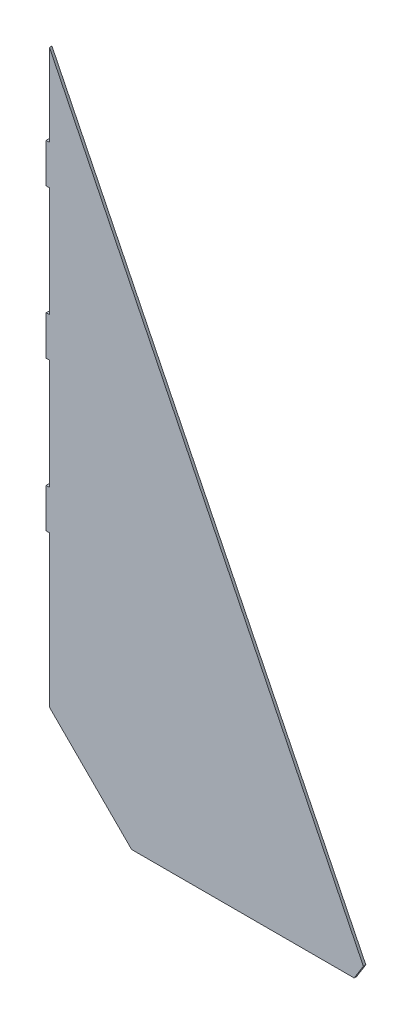
SolidWorks part; units mm, degrees
ref_plane "Front Plane" through (0, 0, 0) normal (0, 0, 1) x (1, 0, 0)
ref_plane "Top Plane" through (0, 0, 0) normal (0, 1, 0) x (1, 0, 0)
ref_plane "Right Plane" through (0, 0, 0) normal (1, 0, 0) x (0, 0, -1)
sketch "Sketch1" plane through (0, 0, 0) normal (0, 0, 1) x (1, 0, 0)
  line L0 (0, 0) -> (0, 297.8632)
  line L1 (0, 297.8632) -> (191.0937, -91.025)
  line L2 (185.5039, -100) -> (50, -100)
  line L3 (0, -50) -> (0, 0)
  line L4 (50, -100) -> (0, -50)
  line L5 (191.0937, -91.025) -> (185.5039, -100)
  point P4 (195.5039, -100)
  point P5 (0, -100)
  dimension "D2" = 100
extrude "Boss-Extrude1" add sketch "Sketch1" along normal blind 1.5
sketch "Sketch7" plane through (0, 0, 0) normal (-1, 0, 0) x (0, 0, 1)
  line L0 (0, 247.8632) -> (1.5, 247.8632)
  line L1 (0, 297.8632) -> (0, -50) construction
  line L2 (1.5, 297.8632) -> (1.5, -50) construction
  line L3 (1.5, 247.8632) -> (1.5, 223.8632)
  line L4 (1.5, 223.8632) -> (0, 223.8632)
  line L5 (0, 223.8632) -> (0, 247.8632)
  line L6 (1.5, 297.8632) -> (0, 297.8632) construction
  line L7 (-31.75, 1.9834) -> (33.25, 1.9834) construction
  line L8 (0, 156.9834) -> (1.5, 156.9834)
  line L9 (0, 156.9834) -> (0, 132.9834)
  line L10 (0, 132.9834) -> (1.5, 132.9834)
  line L11 (1.5, 156.9834) -> (1.5, 132.9834)
  line L12 (0, 41.9834) -> (1.5, 41.9834)
  line L13 (0, 41.9834) -> (0, 65.9834)
  line L14 (0, 65.9834) -> (1.5, 65.9834)
  line L15 (1.5, 41.9834) -> (1.5, 65.9834)
  dimension "D1" = 24
  dimension "D2" = 50
  dimension "D3" = 24
  dimension "D4" = 24
  dimension "D5" = 40
  dimension "D6" = 67
extrude "Boss-Extrude3" add sketch "Sketch7" along normal blind 2
